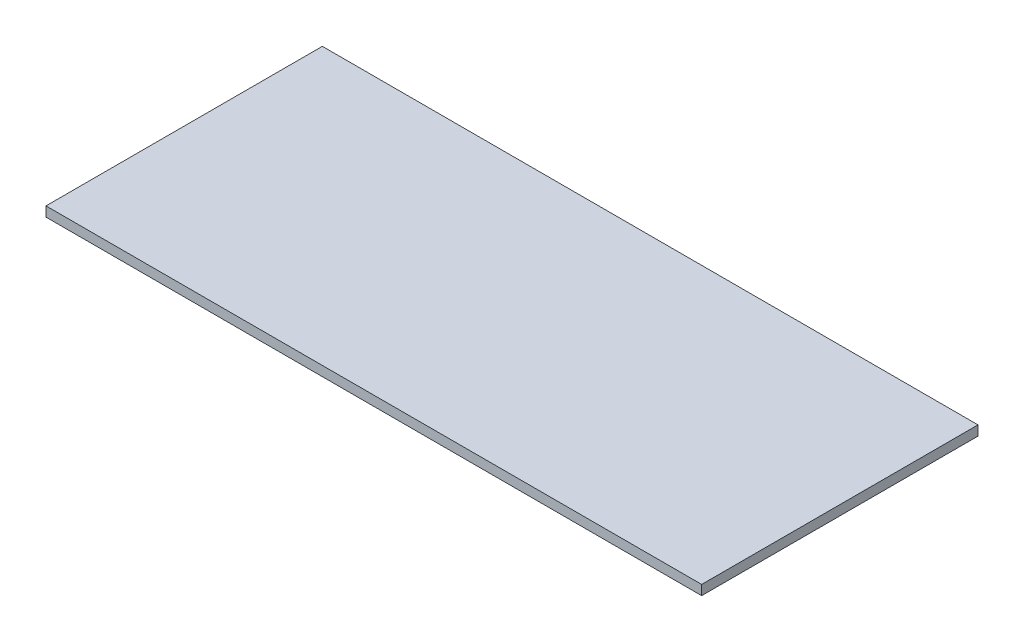
SolidWorks part; units mm, degrees
ref_plane "Front Plane" through (0, 0, 0) normal (0, 0, 1) x (1, 0, 0)
ref_plane "Top Plane" through (0, 0, 0) normal (0, 1, 0) x (1, 0, 0)
ref_plane "Right Plane" through (0, 0, 0) normal (1, 0, 0) x (0, 0, -1)
sketch "Esquisse1" plane through (0, 0, 0) normal (0, 1, 0) x (1, 0, 0)
  line L1 (-605, 255) -> (605, 255)
  line L2 (-605, 255) -> (-605, -255)
  line L3 (-605, -255) -> (605, -255)
  line L4 (605, 255) -> (605, -255)
  line L5 (-605, 255) -> (605, -255) construction
  line L6 (-605, -255) -> (605, 255) construction
  point P0 (0, 0)
extrude "Boss.-Extru.1" add sketch "Esquisse1" along normal blind 18 contours L2 L3 L4 L1
